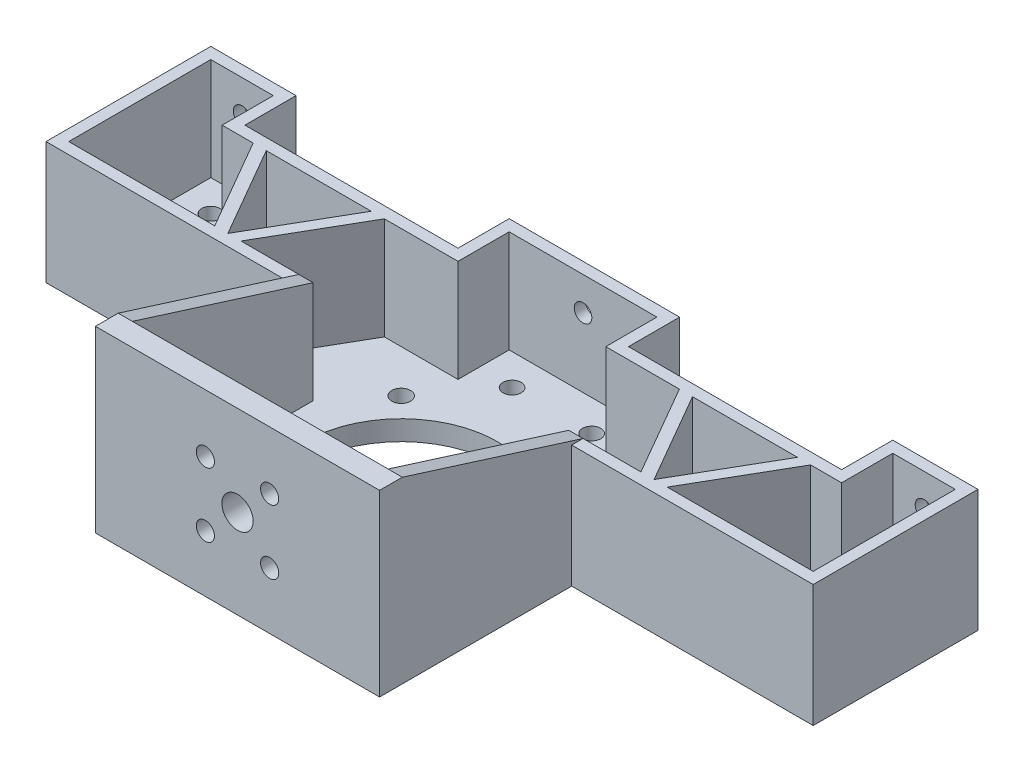
SolidWorks part; units mm, degrees
ref_plane "前视基准面" through (0, 0, 0) normal (0, 0, 1) x (1, 0, 0)
ref_plane "上视基准面" through (0, 0, 0) normal (0, 1, 0) x (1, 0, 0)
ref_plane "右视基准面" through (0, 0, 0) normal (1, 0, 0) x (0, 0, -1)
sketch "草图2" plane through (0, 0, 0) normal (0, 1, 0) x (1, 0, 0)
  line L15 (-42.5, 33.8) -> (-42.5, 62.8)
  line L16 (-42.5, 62.8) -> (-27.5, 62.8)
  line L17 (-27.5, 62.8) -> (-27.5, 53.8)
  line L18 (-27.5, 53.8) -> (10, 53.8)
  line L19 (10, 53.8) -> (10, 62.8)
  line L20 (10, 62.8) -> (40, 62.8)
  line L21 (40, 62.8) -> (40, 53.8)
  line L22 (40, 53.8) -> (77.5, 53.8)
  line L23 (77.5, 53.8) -> (77.5, 62.8)
  line L24 (77.5, 62.8) -> (92.5, 62.8)
  line L25 (92.5, 62.8) -> (92.5, 33.8)
  line L27 (-42.5, 33.8) -> (0, 33.8)
  line L28 (0, 33.8) -> (0, 0)
  line L29 (0, 0) -> (50, 0)
  line L30 (50, 0) -> (50, 33.8)
  line L31 (50, 33.8) -> (92.5, 33.8)
  line L32 (25, -43.9837) -> (25, 74.5213) construction
  line L33 (85, 58.3) -> (85, -14.8283) construction
  line L34 (-35, 58.3) -> (-35, -33.736) construction
  circle A1 centre (-35, 55.3122) radius 1.6
  circle A3 centre (85, 55.3122) radius 1.6
  circle A6 centre (18, 55.3122) radius 1.6
  circle A7 centre (32, 55.3122) radius 1.6
  circle A10 centre (25, 28.8) radius 17
  circle A11 centre (40.5, 44.3) radius 1.65
  circle A12 centre (40.5, 13.3) radius 1.65
  circle A13 centre (9.5, 13.3) radius 1.65
  circle A14 centre (9.5, 44.3) radius 1.65
  point P0 (-35, 55.3122)
  point P1 (85, 55.3122)
  point P2 (85, 58.3)
  point P3 (-35, 58.3)
  point P6 (18, 55.3122)
  point P50 (25, 28.8)
  dimension "D2" = 120
  dimension "D20" = 3.2
  dimension "D22" = 34
  dimension "D7" = 28.8
  dimension "D10" = 50
  dimension "D11" = 25
  dimension "D14" = 3.3
  dimension "D17" = 31
  dimension "D4" = 14
  dimension "D6" = 25
  dimension "D9" = 30
  dimension "D12" = 15
  dimension "D13" = 15
  dimension "D15" = 20
  dimension "D16" = 4
  dimension "D18" = 4.5
  dimension "D19" = 25
extrude "凸台-拉伸2" add sketch "草图2" along normal blind 3.5
sketch "草图6" plane through (0, 3.5, 0) normal (0, 1, 0) x (1, 0, 0)
  line L9 (25, 28.8) -> (25, -10.253) construction
  line L12 (10, 53.8) -> (-27.5, 53.8) construction
  line L13 (10, 62.8) -> (10, 53.8) construction
  line L14 (40, 62.8) -> (10, 62.8) construction
  line L15 (40, 53.8) -> (40, 62.8) construction
  line L16 (77.5, 53.8) -> (40, 53.8) construction
  line L17 (77.5, 62.8) -> (77.5, 53.8) construction
  line L18 (92.5, 62.8) -> (77.5, 62.8) construction
  line L19 (92.5, 33.8) -> (92.5, 62.8) construction
  line L20 (50, 33.8) -> (92.5, 33.8) construction
  line L21 (50, 0) -> (50, 33.8) construction
  line L22 (0, 0) -> (50, 0) construction
  line L23 (0, 33.8) -> (0, 0) construction
  line L24 (-42.5, 33.8) -> (0, 33.8) construction
  line L25 (-42.5, 62.8) -> (-42.5, 33.8) construction
  line L26 (-27.5, 53.8) -> (-27.5, 62.8) construction
  line L27 (-27.5, 62.8) -> (-42.5, 62.8) construction
  line L28 (10, 53.8) -> (-27.5, 53.8)
  line L29 (10, 62.8) -> (10, 53.8)
  line L30 (40, 62.8) -> (10, 62.8)
  line L31 (40, 53.8) -> (40, 62.8)
  line L32 (77.5, 53.8) -> (40, 53.8)
  line L33 (77.5, 62.8) -> (77.5, 53.8)
  line L34 (92.5, 62.8) -> (77.5, 62.8)
  line L35 (92.5, 33.8) -> (92.5, 62.8)
  line L36 (50, 33.8) -> (92.5, 33.8)
  line L37 (50, 0) -> (50, 33.8)
  line L38 (0, 0) -> (50, 0)
  line L39 (0, 33.8) -> (0, 0)
  line L40 (-42.5, 33.8) -> (0, 33.8)
  line L41 (-42.5, 62.8) -> (-42.5, 33.8)
  line L42 (-27.5, 53.8) -> (-27.5, 62.8)
  line L43 (-27.5, 62.8) -> (-42.5, 62.8)
  line L44 (12, 51.8) -> (-29.5, 51.8)
  line L45 (-29.5, 51.8) -> (-29.5, 60.8)
  line L46 (-29.5, 60.8) -> (-40.5, 60.8)
  line L47 (-40.5, 60.8) -> (-40.5, 35.8)
  line L48 (-40.5, 35.8) -> (2.5, 35.8)
  line L49 (2.5, 35.8) -> (2.5, 4)
  line L50 (2.5, 4) -> (47.5, 4)
  line L51 (47.5, 4) -> (47.5, 35.8)
  line L52 (47.5, 35.8) -> (90.5, 35.8)
  line L53 (90.5, 35.8) -> (90.5, 60.8)
  line L54 (90.5, 60.8) -> (79.5, 60.8)
  line L55 (79.5, 60.8) -> (79.5, 51.8)
  line L56 (79.5, 51.8) -> (38, 51.8)
  line L57 (38, 51.8) -> (38, 60.8)
  line L58 (38, 60.8) -> (12, 60.8)
  line L59 (12, 60.8) -> (12, 51.8)
  dimension "D1" = 4
  dimension "D2" = 2
  dimension "D3" = 2
  dimension "D4" = 2
  dimension "D5" = 2
  dimension "D6" = 2
  dimension "D7" = 2
  dimension "D8" = 2
  dimension "D9" = 2
  dimension "D10" = 2
  dimension "D11" = 2
  dimension "D12" = 2
  dimension "D13" = 2
  dimension "D14" = 2.5
  dimension "D15" = 2.5
  dimension "D16" = 2
extrude "凸台-拉伸3" add sketch "草图6" along normal blind 18
sketch "草图11" plane through (0, 21.5, 0) normal (0, 1, 0) x (1, 0, 0)
  line L0 (2.5, 35.8) -> (2.5, 4)
  line L1 (2.5, 4) -> (47.5, 4)
  line L2 (47.5, 4) -> (47.5, 35.8)
  line L3 (47.5, 35.8) -> (50, 35.8)
  line L4 (47.5, 35.8) -> (90.5, 35.8) construction
  line L5 (50, 35.8) -> (50, 0)
  line L6 (50, 0) -> (50, 33.8) construction
  line L7 (50, 0) -> (0, 0)
  line L8 (0, 0) -> (0, 35.8)
  line L9 (-40.5, 35.8) -> (2.5, 35.8) construction
  line L10 (0, 35.8) -> (2.5, 35.8)
extrude "凸台-拉伸4" add sketch "草图11" along normal blind 10
sketch "草图12" plane through (0, 0, 0) normal (-1, 0, 0) x (0, 0, 1)
  line L0 (-35.8, 21.5) -> (-4, 31.5)
  line L1 (-35.8, 31.5) -> (0, 31.5) construction
  line L2 (-4, 31.5) -> (-35.8, 31.5)
  line L3 (-35.8, 31.5) -> (-35.8, 21.5)
  line L4 (0, 31.5) -> (0, 0) construction
  dimension "D1" = 4
extrude "切除-拉伸5" cut sketch "草图12" against normal through all
sketch "草图10" plane through (0, 0, 0) normal (0, 0, 1) x (1, 0, 0)
  line L0 (25, 37.2917) -> (25, -8.8083) construction
  line L5 (0, 0) -> (50, 0) construction
  line L6 (0, 31.5) -> (0, 0) construction
  line L7 (50, 31.5) -> (50, 0) construction
  circle A0 centre (25, 15.6569) radius 2.75
  circle A1 centre (30.6569, 21.3137) radius 1.6
  circle A2 centre (30.6569, 10) radius 1.6
  circle A3 centre (19.3431, 10) radius 1.6
  circle A4 centre (19.3431, 21.3137) radius 1.6
  point P19 (25, 15.6569)
  dimension "D1" = 10
  dimension "D2" = 5.5
  dimension "D3" = 3.2
  dimension "D4" = 8
  dimension "D5" = 4
extrude "切除-拉伸4" cut sketch "草图10" against normal blind 5
sketch "草图13" plane through (0, 3.5, 0) normal (0, 1, 0) x (1, 0, 0)
  line L0 (-21.7376, 51.8) -> (-12.5, 35.8)
  line L1 (12, 51.8) -> (-29.5, 51.8) construction
  line L2 (-40.5, 35.8) -> (0, 35.8) construction
  line L3 (-12.5, 35.8) -> (-3.2624, 51.8)
  line L5 (-21.7376, 51.8) -> (-24.047, 51.8)
  line L6 (12, 51.8) -> (-29.5, 51.8) construction
  line L7 (-24.047, 51.8) -> (-14.8094, 35.8)
  line L8 (-27.5, 53.8) -> (-27.5, 62.8) construction
  line L9 (-14.8094, 35.8) -> (-12.5, 35.8)
  line L10 (-3.2624, 51.8) -> (-0.953, 51.8)
  line L11 (-0.953, 51.8) -> (-10.1906, 35.8)
  line L12 (-10.1906, 35.8) -> (-12.5, 35.8)
  line L13 (-12.5, 35.8) -> (-12.5, 56.0294) construction
  line L14 (0, 35.8) -> (0, 4) construction
  line L15 (25, 62.8) -> (25, -17.4304) construction
  line L16 (40, 62.8) -> (10, 62.8) construction
  line L17 (60.1906, 35.8) -> (62.5, 35.8)
  line L18 (50.953, 51.8) -> (60.1906, 35.8)
  line L19 (53.2624, 51.8) -> (50.953, 51.8)
  line L20 (62.5, 35.8) -> (53.2624, 51.8)
  line L21 (64.8094, 35.8) -> (62.5, 35.8)
  line L22 (74.047, 51.8) -> (64.8094, 35.8)
  line L23 (71.7376, 51.8) -> (74.047, 51.8)
  line L24 (71.7376, 51.8) -> (62.5, 35.8)
  line M13 (12, 51.8) -> (-29.5, 51.8)
  line M17 (-40.5, 35.8) -> (2.5, 35.8)
  line M21 (47.5, 35.8) -> (90.5, 35.8)
  line M25 (79.5, 51.8) -> (38, 51.8)
  dimension "D1" = 2
  dimension "D2" = 60
  dimension "D3" = 15
  dimension "D4" = 12.5
extrude "凸台-拉伸5" add sketch "草图13" along normal up to surface (18 mm away) contours L7 L0 M13 M17 | L11 L3 M13 M17 | L20 L18 M21 M25 | L24 L22 M25 M21 up to face at (25, 21.5, -51.5143)
sketch "草图14" plane through (0, 0, -62.8) normal (0, 0, -1) x (-1, 0, 0)
  line L0 (-25, 46.072) -> (-25, -18.623) construction
  line L1 (42.5, 21.5) -> (42.5, 0) construction
  line L2 (-92.5, 21.5) -> (-92.5, 0) construction
  circle A0 centre (35, 15.6569) radius 1.55
  circle A1 centre (-85, 15.6569) radius 1.55
  circle A2 centre (-25, 15.6569) radius 1.55
  point P10 (0, 0)
  dimension "D1" = 3.1
  dimension "D2" = 120
  dimension "D4" = 3.1
extrude "切除-拉伸6" cut sketch "草图14" against normal blind 10
sketch "草图16" plane through (0, 0, 0) normal (-1, 0, 0) x (0, 0, 1)
  line L0 (-19.8, 26.5314) -> (-19.8, 18.5)
  line L1 (-35.8, 21.5) -> (-4, 31.5) construction
  line L2 (-19.8, 18.5) -> (-35.8, 18.5)
  line L3 (-35.8, 21.5) -> (-35.8, 18.5)
  line L4 (-35.8, 21.5) -> (-19.8, 26.5314)
  dimension "D1" = 16
  dimension "D2" = 3
